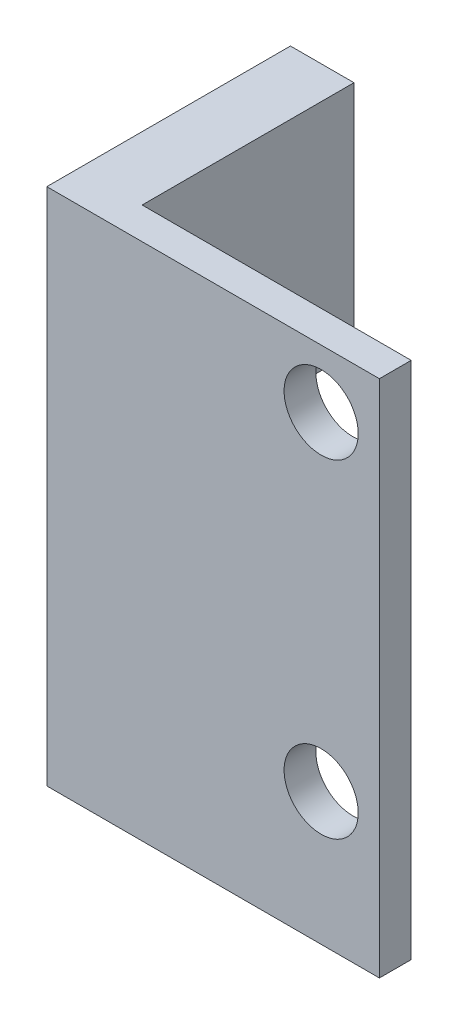
SolidWorks part; units mm, degrees
ref_plane "Plan de face" through (0, 0, 0) normal (0, 0, 1) x (1, 0, 0)
ref_plane "Plan de dessus" through (0, 0, 0) normal (0, 1, 0) x (1, 0, 0)
ref_plane "Plan de droite" through (0, 0, 0) normal (1, 0, 0) x (0, 0, -1)
sketch "Esquisse1" plane through (0, 0, 0) normal (0, 0, 1) x (1, 0, 0)
  line L0 (-2.75, 23.5) -> (0, 23.5) construction
  line L1 (0, 0) -> (-15.7, 0)
  line L2 (0, 0) -> (0, 24.5)
  line L3 (0, 24.5) -> (-15.7, 24.5)
  line L4 (-15.7, 0) -> (-15.7, 24.5)
  line L5 (-2.75, 20) -> (0, 20) construction
  line L6 (-2.75, 8) -> (0, 8) construction
  line L7 (-2.75, 4.5) -> (0, 4.5) construction
  line L8 (-1, 21.75) -> (-1, 24.5) construction
  line L9 (-1, 6.25) -> (-1, 0) construction
  circle A0 centre (-2.75, 21.75) radius 1.75
  circle A1 centre (-2.75, 6.25) radius 1.75
  dimension "D3" = 3.5
  dimension "D4" = 3.5
  dimension "D7" = 12
  dimension "D1" = 24.5
  dimension "D2" = 15.7
  dimension "D5" = 1
  dimension "D6" = 1
  dimension "D8" = 1
extrude "Boss.-Extru.1" add sketch "Esquisse1" along normal blind 1.5
sketch "Esquisse2" plane through (0, 0, 0) normal (0, 0, -1) x (-1, 0, 0)
  line L1 (15.7, 24.5) -> (12.7, 24.5)
  line L2 (15.7, 24.5) -> (15.7, 13.5)
  line L3 (15.7, 13.5) -> (12.7, 13.5)
  line L4 (12.7, 24.5) -> (12.7, 13.5)
  dimension "D1" = 11
  dimension "D2" = 3
extrude "Boss.-Extru.2" add sketch "Esquisse2" along normal blind 10
